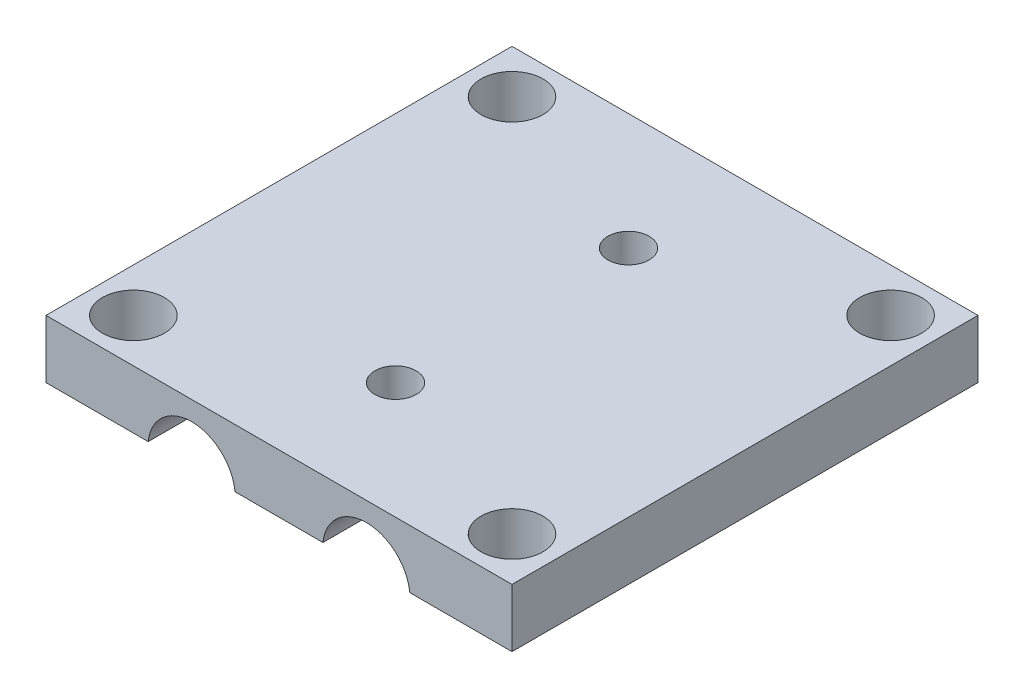
SolidWorks part; units mm, degrees
material "Copper"
ref_plane "Front Plane" through (0, 0, 0) normal (0, 0, 1) x (1, 0, 0)
ref_plane "Top Plane" through (0, 0, 0) normal (0, 1, 0) x (1, 0, 0)
ref_plane "Right Plane" through (0, 0, 0) normal (1, 0, 0) x (0, 0, -1)
sketch "Sketch1" plane through (0, 0, 0) normal (0, 1, 0) x (1, 0, 0)
  line L1 (-25.4, 25.4) -> (25.4, 25.4)
  line L2 (-25.4, 25.4) -> (-25.4, -25.4)
  line L3 (-25.4, -25.4) -> (25.4, -25.4)
  line L4 (25.4, 25.4) -> (25.4, -25.4)
  dimension "D1" = 50.8
  dimension "D2" = 50.8
  dimension "D3" = 25.4
  dimension "D4" = 25.4
extrude "Boss-Extrude1" add sketch "Sketch1" along normal blind 6.35
sketch "Sketch2" plane through (0, 0, 25.4) normal (0, 0, 1) x (1, 0, 0)
  circle A0 centre (-9.525, -0.508) radius 4.7625
  circle A1 centre (9.525, -0.508) radius 4.7625
  dimension "D1" = 9.525
  dimension "D2" = 9.525
extrude "Cut-Extrude1" cut sketch "Sketch2" against normal through all
hole_wizard "1/4 Clearance Hole1" positions "Sketch5" profile "Sketch4" hole size "1/4" standard "ANSI Inch" end condition through all
sketch "Sketch5" plane through (0, 6.35, 0) normal (0, 1, 0) x (1, 0, 0)
  point P0 (-20.6375, -20.6375)
  point P2 (-20.6375, 20.6375)
  point P4 (20.6375, 20.6375)
  point P6 (20.6375, -20.6375)
sketch "Sketch4" plane through (-20.6375, 6.35, 20.6375) normal (1, 0, 0) x (0, 0, 1)
  line L0 (0, 0) -> (0, 6.35)
  line L1 (0, 6.35) -> (3.3782, 6.35)
  line L2 (3.3782, 6.35) -> (3.3782, 0)
  line L5 (3.3782, 0) -> (0, 0)
  line L11 (0, -6.35) -> (0, 107.95) construction
  dimension "Thru Hole Dia." = 6.7564
  dimension "Thru Hole Depth" = 6.35
hole_wizard "#8 Clearance Hole1" positions "Sketch9" profile "Sketch8" hole size "#8" standard "ANSI Inch" end condition through all
sketch "Sketch9" plane through (0, 6.35, 0) normal (0, 1, 0) x (1, 0, 0)
  point P0 (0, 12.7)
  point P2 (0, -12.7)
sketch "Sketch8" plane through (0, 6.35, -12.7) normal (1, 0, 0) x (0, 0, 1)
  line L0 (0, 0) -> (0, 6.35)
  line L1 (0, 6.35) -> (2.2479, 6.35)
  line L2 (2.2479, 6.35) -> (2.2479, 0)
  line L5 (2.2479, 0) -> (0, 0)
  line L11 (0, -6.35) -> (0, 107.95) construction
  dimension "Thru Hole Dia." = 4.4958
  dimension "Thru Hole Depth" = 6.35
